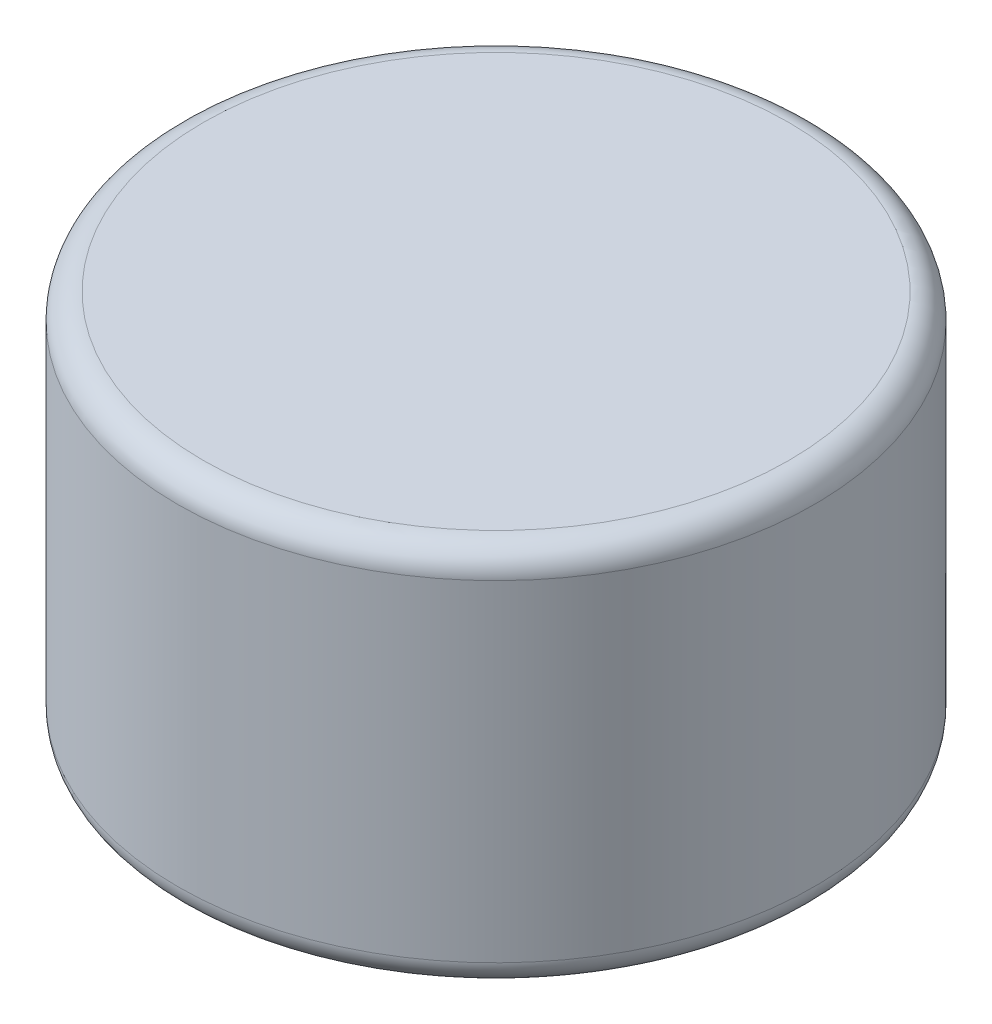
SolidWorks part; units mm, degrees
ref_plane "Front Plane" through (0, 0, 0) normal (0, 0, 1) x (1, 0, 0)
ref_plane "Top Plane" through (0, 0, 0) normal (0, 1, 0) x (1, 0, 0)
ref_plane "Right Plane" through (0, 0, 0) normal (1, 0, 0) x (0, 0, -1)
sketch "Sketch1" plane through (0, 0, 0) normal (0, 1, 0) x (1, 0, 0)
  circle A0 centre (0, 0) radius 2.5
extrude "Boss-Extrude1" add sketch "Sketch1" along normal blind 3
fillet "Fillet1" radius 0.2 2 edges at (0, 0, 2.5) (0, 3, 2.5)
